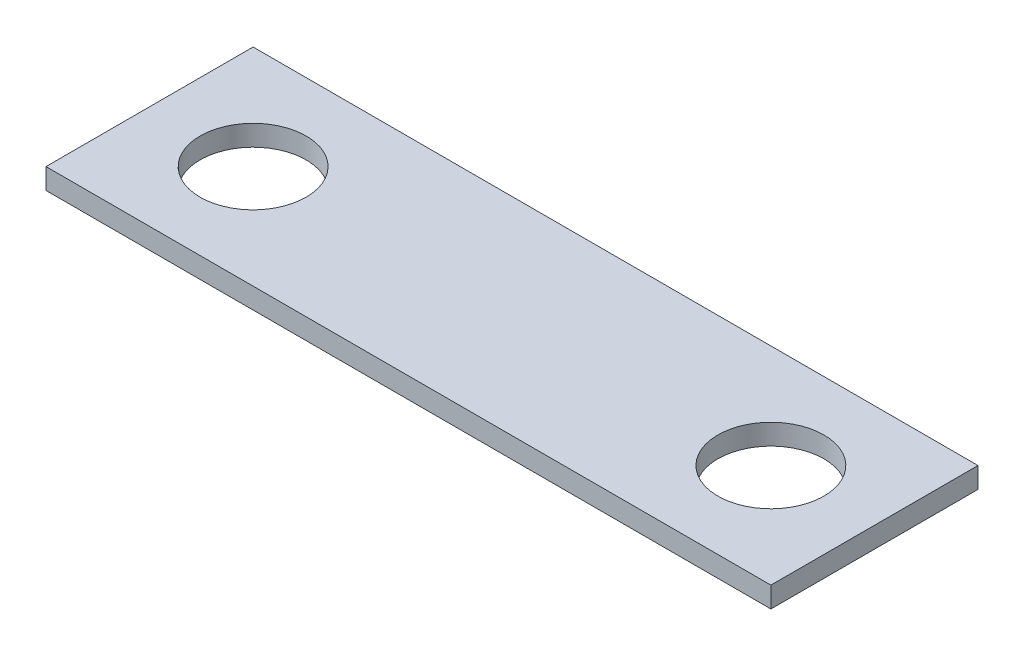
SolidWorks part; units mm, degrees
ref_plane "Front Plane" through (0, 0, 0) normal (0, 0, 1) x (1, 0, 0)
ref_plane "Top Plane" through (0, 0, 0) normal (0, 1, 0) x (1, 0, 0)
ref_plane "Right Plane" through (0, 0, 0) normal (1, 0, 0) x (0, 0, -1)
sketch "Sketch1" plane through (0, 0, 0) normal (0, 1, 0) x (1, 0, 0)
  line L0 (22.225, 12.7) -> (22.225, 0) construction
  line L1 (0, 0) -> (44.45, 0)
  line L2 (0, 0) -> (0, 12.7)
  line L3 (0, 12.7) -> (44.45, 12.7)
  line L4 (44.45, 0) -> (44.45, 12.7)
  circle A0 centre (6.35, 6.35) radius 3.2512
  circle A1 centre (38.1, 6.35) radius 3.2512
  dimension "D3" = 6.5024
  dimension "D1" = 31.75
  dimension "D2" = 12.7
  dimension "D4" = 6.35
  dimension "D5" = 6.35
extrude "Boss-Extrude1" add sketch "Sketch1" along normal blind 1.27
